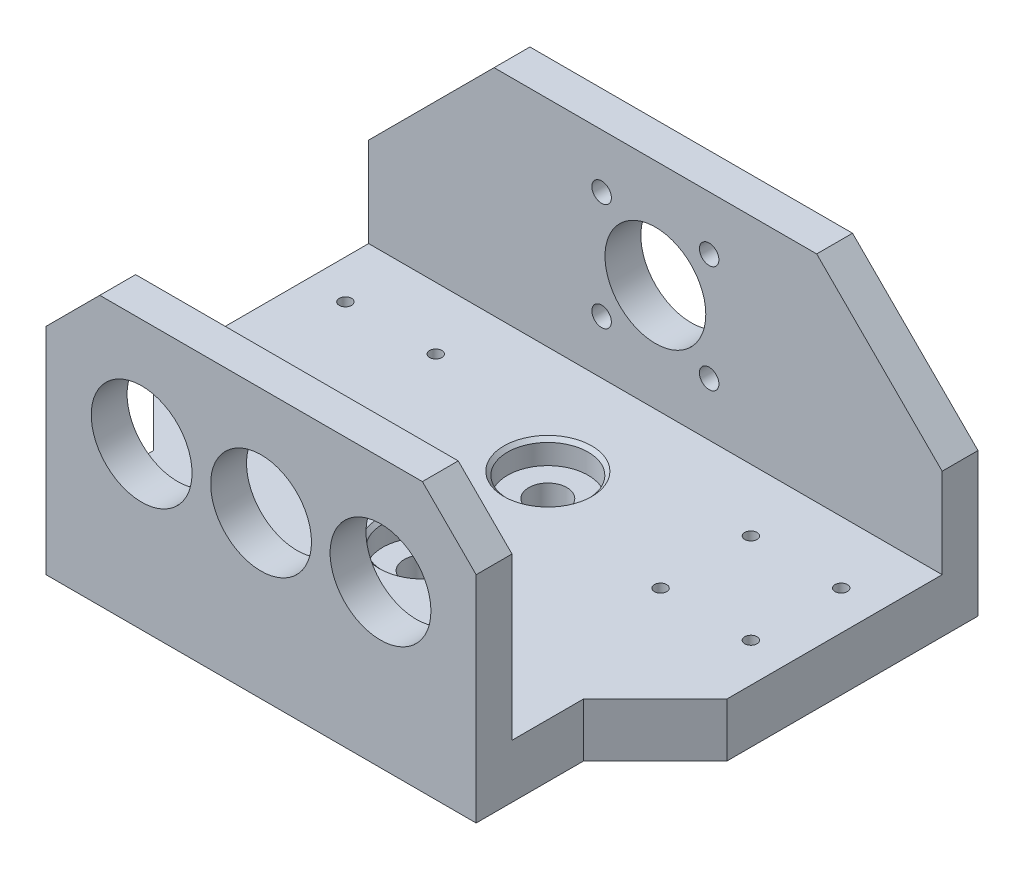
SolidWorks part; units mm, degrees
ref_plane "Front Plane" through (0, 0, 0) normal (0, 0, 1) x (1, 0, 0)
ref_plane "Top Plane" through (0, 0, 0) normal (0, 1, 0) x (1, 0, 0)
ref_plane "Right Plane" through (0, 0, 0) normal (1, 0, 0) x (0, 0, -1)
sketch "Sketch1" plane through (0, 0, 0) normal (0, 1, 0) x (1, 0, 0)
  line L1 (0, 0) -> (101.6, 0)
  line L2 (0, 0) -> (0, 76.2)
  line L3 (0, 76.2) -> (101.6, 76.2)
  line L4 (101.6, 0) -> (101.6, 76.2)
  dimension "D1" = 76.2
  dimension "D2" = 101.6
extrude "Boss-Extrude1" add sketch "Sketch1" along normal blind 50.8 contours L3 L4 L1 L2
ref_plane "Plane1" through (0, 0, -38.1) normal (0, 0, 1) x (1, 0, 0)
sketch "Sketch9" plane through (0, 0, -38.1) normal (0, 0, 1) x (1, 0, 0)
  line L0 (0, 50.8) -> (101.6, 50.8) construction
  line L1 (0, 50.8) -> (101.6, 50.8)
  line L2 (50.8, 50.8) -> (50.8, 0) construction
  line L3 (0, 50.8) -> (0, 9.525)
  line L4 (0, 9.525) -> (101.6, 9.525)
  line L5 (101.6, 50.8) -> (101.6, 9.525)
  line L6 (0, 0) -> (101.6, 0) construction
  line L7 (0, 0) -> (101.6, 0) construction
  point P8 (50.8, 9.525)
  dimension "D1" = 9.525
extrude "Cut-Extrude1" cut sketch "Sketch9" against normal blind 31.75 and the other way blind 31.75
hole_wizard "45/64 (0.70313) Diameter Hole1" positions "Sketch4" profile "Sketch5" hole size "45/64" standard "ANSI Inch" end condition through all
sketch "Sketch4" plane through (0, 0, 0) normal (0, 0, 1) x (1, 0, 0)
  line L1 (0, 28.5242) -> (101.6, 28.5242) construction
  line L2 (0, 50.8) -> (0, 0) construction
  line L3 (101.6, 50.8) -> (101.6, 0) construction
  line L5 (0, 9.525) -> (101.6, 9.525) construction
  line L6 (0, 9.525) -> (101.6, 9.525) construction
  point P7 (50.8, 28.5242)
  point P16 (50.8, 28.5242)
  dimension "D1" = 18.9992
sketch "Sketch5" plane through (50.8, 28.5242, 0) normal (1, 0, 0) x (0, -1, 0)
  line L0 (0, 0) -> (0, 76.2)
  line L1 (0, 76.2) -> (8.9298, 76.2)
  line L2 (8.9298, 76.2) -> (8.9298, 0)
  line L5 (8.9298, 0) -> (0, 0)
  line L11 (0, -6.35) -> (0, 107.95) construction
  dimension "Thru Hole Dia." = 17.8595
  dimension "Thru Hole Depth" = 76.2
hole_wizard "45/64 (0.70313) Diameter Hole2" positions "Sketch7" profile "Sketch6" hole size "45/64" standard "ANSI Inch"
sketch "Sketch7" plane through (0, 0, 0) normal (0, 0, 1) x (1, 0, 0)
  line L2 (0, 28.5242) -> (152.4, 28.5242) construction
  line L5 (50.8, 28.5242) -> (50.8, 0) construction
  line L6 (0, 0) -> (101.6, 0) construction
  circle A1 centre (50.8, 28.5242) radius 8.9298 construction
  point P0 (29.6418, 28.5242)
  point P2 (71.9582, 28.5242)
  dimension "D1" = 21.1582
  dimension "D2" = 21.1582
sketch "Sketch6" plane through (29.6418, 28.5242, 0) normal (1, 0, 0) x (0, -1, 0)
  line L0 (0, 0) -> (0, 30.7655)
  line L1 (0, 30.7655) -> (8.9298, 25.4)
  line L2 (8.9298, 25.4) -> (8.9298, 0)
  line L5 (8.9298, 0) -> (0, 0)
  line L10 (0, 30.7655) -> (-8.9298, 25.4) construction
  line L11 (0, -6.35) -> (0, 107.95) construction
  dimension "Hole Dia." = 17.8595
  dimension "Hole Depth" = 25.4
  dimension "Drill Angle" = 118
hole_wizard "CBORE for 1/4 Binding Head Machine Screw1" positions "Sketch13" profile "Sketch14" counterbore size "1/4" standard "ANSI Inch" end condition through all
sketch "Sketch13" plane through (0, 9.525, 0) normal (0, 1, 0) x (1, 0, 0)
  line L0 (50.8, 69.85) -> (50.8, 6.35) construction
  line L1 (0, 69.85) -> (101.6, 69.85) construction
  line L2 (0, 6.35) -> (101.6, 6.35) construction
  line L3 (0, 76.2) -> (101.6, 76.2) construction
  line L4 (0, 76.2) -> (101.6, 76.2) construction
  point P9 (50.8, 50.8)
  point P11 (50.8, 28.702)
  dimension "D1" = 22.098
  dimension "D2" = 25.4
sketch "Sketch14" plane through (50.8, 9.525, -50.8) normal (1, 0, 0) x (0, 0, 1)
  line L0 (0, 0) -> (0, 9.525)
  line L1 (0, 9.525) -> (3.3782, 9.525)
  line L3 (3.3782, 9.525) -> (3.3782, 4.191)
  line L4 (7.1437, 4.191) -> (3.3782, 4.191)
  line L5 (7.1437, 4.191) -> (7.1438, 0.635)
  line L6 (7.1438, 0.635) -> (7.7788, 0)
  line L7 (7.7788, 0) -> (0, 0)
  line L8 (-7.1438, 0.635) -> (-7.7788, 0) construction
  line L11 (0, -6.35) -> (0, 107.95) construction
  dimension "Thru Hole Dia." = 6.7564
  dimension "Thru Hole Depth" = 9.525
  dimension "C'Bore Dia." = 14.2875
  dimension "C'Bore Depth" = 4.191
  dimension "Near C'Sink Dia." = 15.5575
  dimension "Near C'Sink Angle" = 90
sketch "Sketch17" plane through (0, 0, 0) normal (0, 0, 1) x (1, 0, 0)
  line L0 (0, 25.4) -> (22.225, 47.625)
  line L1 (0, 50.8) -> (0, 0) construction
  line L2 (22.225, 47.625) -> (79.375, 47.625)
  line L3 (79.375, 47.625) -> (101.6, 25.4)
  line L4 (101.6, 50.8) -> (101.6, 0) construction
  line L5 (0, 25.4) -> (0, 50.8)
  line L6 (0, 50.8) -> (101.6, 50.8)
  line L7 (101.6, 50.8) -> (101.6, 25.4)
  dimension "D1" = 3.175
  dimension "D2" = 45
  dimension "D3" = 22.225
extrude "Cut-Extrude3" cut sketch "Sketch17" against normal through all
hole_wizard "#8-32 Tapped Hole1" positions "Sketch19" profile "Sketch20" tap size "#8-32" standard "ANSI Inch"
sketch "Sketch19" plane through (0, 0, -76.2) normal (0, 0, -1) x (-1, 0, 0)
  line L1 (-60.325, 18.9992) -> (-41.275, 18.9992) construction
  line L2 (-60.325, 18.9992) -> (-60.325, 38.0492) construction
  line L3 (-60.325, 38.0492) -> (-41.275, 38.0492) construction
  line L4 (-41.275, 18.9992) -> (-41.275, 38.0492) construction
  line L5 (-60.325, 18.9992) -> (-41.275, 38.0492) construction
  line L6 (-60.325, 38.0492) -> (-41.275, 18.9992) construction
  circle A0 centre (-50.8, 28.5242) radius 19.05 construction
  point P5 (-41.275, 38.0492)
  point P112 (-60.325, 18.9992)
  point P113 (-60.325, 38.0492)
  point P114 (-41.275, 18.9992)
  dimension "D1" = 38.1
  dimension "D2" = 19.05
sketch "Sketch20" plane through (41.275, 38.0492, -76.2) normal (1, 0, 0) x (0, 1, 0)
  line L0 (0, 0) -> (0, 6.35)
  line L1 (0, 6.35) -> (1.7272, 6.35)
  line L2 (1.7272, 6.35) -> (1.7272, 0)
  line L5 (1.7272, 0) -> (0, 0)
  line L11 (0, -6.35) -> (0, 107.95) construction
  dimension "Thru Tap Drill Dia." = 3.4544
  dimension "Thru Tap Drill Depth" = 6.35
cosmetic thread "Hole Thread1" parameters "D2"=4.1656
cosmetic thread "Hole Thread2" parameters "D2"=4.1656
cosmetic thread "Hole Thread3" parameters "D2"=4.1656
cosmetic thread "Hole Thread4" parameters "D2"=4.1656
sketch "Sketch21" plane through (0, 0, 0) normal (0, -1, 0) x (1, 0, 0)
  line L0 (50.8, 0) -> (50.8, -76.2) construction
  line L1 (0, 0) -> (101.6, 0) construction
  line L2 (0, -76.2) -> (101.6, -76.2) construction
  line L3 (0, 0) -> (0, -31.75)
  line L4 (0, 0) -> (0, -76.2) construction
  line L5 (0, -31.75) -> (12.7, -19.05)
  line L6 (12.7, -19.05) -> (12.7, 0)
  line L7 (12.7, 0) -> (0, 0)
  line L8 (88.9, 0) -> (101.6, 0)
  line L9 (88.9, -19.05) -> (88.9, 0)
  line L10 (101.6, -31.75) -> (88.9, -19.05)
  line L11 (101.6, 0) -> (101.6, -31.75)
  dimension "D1" = 45
  dimension "D2" = 12.7
  dimension "D3" = 31.75
extrude "Cut-Extrude4" cut sketch "Sketch21" against normal through all
hole_wizard "#44 (0.086) Diameter Hole1" positions "Sketch23" profile "Sketch22" hole size "#44" standard "ANSI Inch" end condition up to next
sketch "Sketch23" plane through (0, 0, 0) normal (0, -1, 0) x (-1, 0, 0)
  line L0 (-50.8, 76.2) -> (-50.8, 0) construction
  line L1 (0, 76.2) -> (-101.6, 76.2) construction
  line L2 (-12.7, 0) -> (-88.9, 0) construction
  line L4 (-50.8, 50.8518) -> (-14.8844, 50.8518) construction
  line L5 (-14.8844, 50.8518) -> (-14.8844, 58.8518) construction
  line L7 (-22.8844, 58.8518) -> (-6.8844, 58.8518) construction
  line L9 (-22.8844, 42.8518) -> (-6.8844, 42.8518) construction
  line L10 (-78.7156, 58.8518) -> (-94.7156, 58.8518) construction
  line L11 (-78.7156, 42.8518) -> (-94.7156, 42.8518) construction
  line L12 (0, 31.75) -> (0, 76.2) construction
  point P17 (-22.8844, 58.8518)
  point P18 (-6.8844, 58.8518)
  point P20 (-14.8844, 58.8518)
  point P21 (-22.8844, 42.8518)
  point P22 (-6.8844, 42.8518)
  point P23 (-78.7156, 58.8518)
  point P24 (-94.7156, 58.8518)
  point P25 (-78.7156, 42.8518)
  point P26 (-94.7156, 42.8518)
  dimension "D1" = 8
  dimension "D2" = 16
  dimension "D3" = 14.8844
  dimension "D4" = 17.3482
sketch "Sketch22" plane through (22.8844, 0, -58.8518) normal (1, 0, 0) x (0, 0, -1)
  line L0 (0, 0) -> (0, 9.525)
  line L1 (0, 9.525) -> (1.0922, 9.525)
  line L2 (1.0922, 9.525) -> (1.0922, 0)
  line L5 (1.0922, 0) -> (0, 0)
  line L11 (0, -6.35) -> (0, 107.95) construction
  dimension "Thru Hole Dia." = 2.1844
  dimension "Thru Hole Depth" = 9.525
